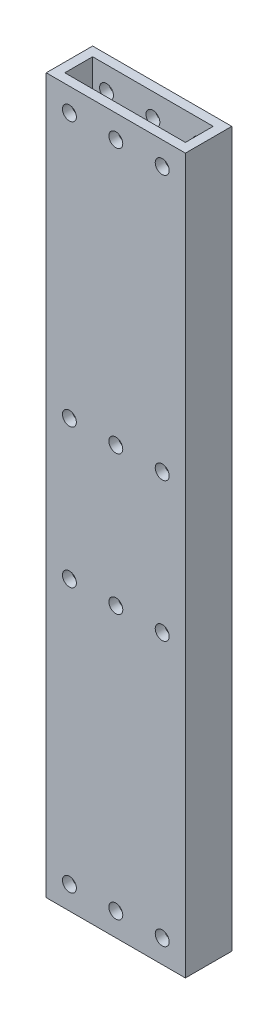
SolidWorks part; units mm, degrees
ref_plane "前视基准面" through (0, 0, 0) normal (0, 0, 1) x (1, 0, 0)
ref_plane "上视基准面" through (0, 0, 0) normal (0, 1, 0) x (1, 0, 0)
ref_plane "右视基准面" through (0, 0, 0) normal (1, 0, 0) x (0, 0, -1)
sketch "草图1" plane through (0, 0, 0) normal (0, 1, 0) x (1, 0, 0)
  line L1 (-15, 5) -> (15, 5)
  line L2 (-15, 5) -> (-15, -5)
  line L3 (-15, -5) -> (15, -5)
  line L4 (15, 5) -> (15, -5)
  line L5 (-15, 5) -> (15, -5) construction
  line L6 (-15, -5) -> (15, 5) construction
  line L7 (-13, 3) -> (13, 3)
  line L8 (-13, 3) -> (-13, -3)
  line L9 (-13, -3) -> (13, -3)
  line L10 (13, 3) -> (13, -3)
  line L11 (-13, 3) -> (13, -3) construction
  line L12 (-13, -3) -> (13, 3) construction
  point P0 (0, 0)
  point P6 (0, 0)
  dimension "D1" = 30
  dimension "D2" = 10
  dimension "D3" = 2
  dimension "D4" = 2
extrude "凸台-拉伸1" add sketch "草图1" along normal mid plane 154
sketch "草图2" plane through (0, 0, 5) normal (0, 0, 1) x (1, 0, 0)
  line L0 (10, 15) -> (-10, 15) construction
  line L1 (15, 77) -> (15, -77) construction
  line L2 (-15, 77) -> (-15, -77) construction
  line L3 (0, 0) -> (25.912, 0) construction
  line L4 (10, 72) -> (-10, 72) construction
  line L5 (-15, 77) -> (15, 77) construction
  circle A0 centre (10, 15) radius 1.5
  circle A1 centre (-10, 15) radius 1.5
  circle A2 centre (0, 15) radius 1.5
  circle A3 centre (10, -15) radius 1.5
  circle A4 centre (0, -15) radius 1.5
  circle A5 centre (-10, -15) radius 1.5
  circle A6 centre (10, 72) radius 1.5
  circle A7 centre (-10, 72) radius 1.5
  circle A8 centre (0, 72) radius 1.5
  circle A9 centre (-10, -72) radius 1.5
  circle A10 centre (0, -72) radius 1.5
  circle A11 centre (10, -72) radius 1.5
  dimension "D1" = 3
  dimension "D6" = 3
  dimension "D2" = 5
  dimension "D3" = 5
  dimension "D4" = 5
  dimension "D5" = 5
  dimension "D7" = 10
  dimension "D8" = 10
extrude "切除-拉伸1" cut sketch "草图2" against normal through all
